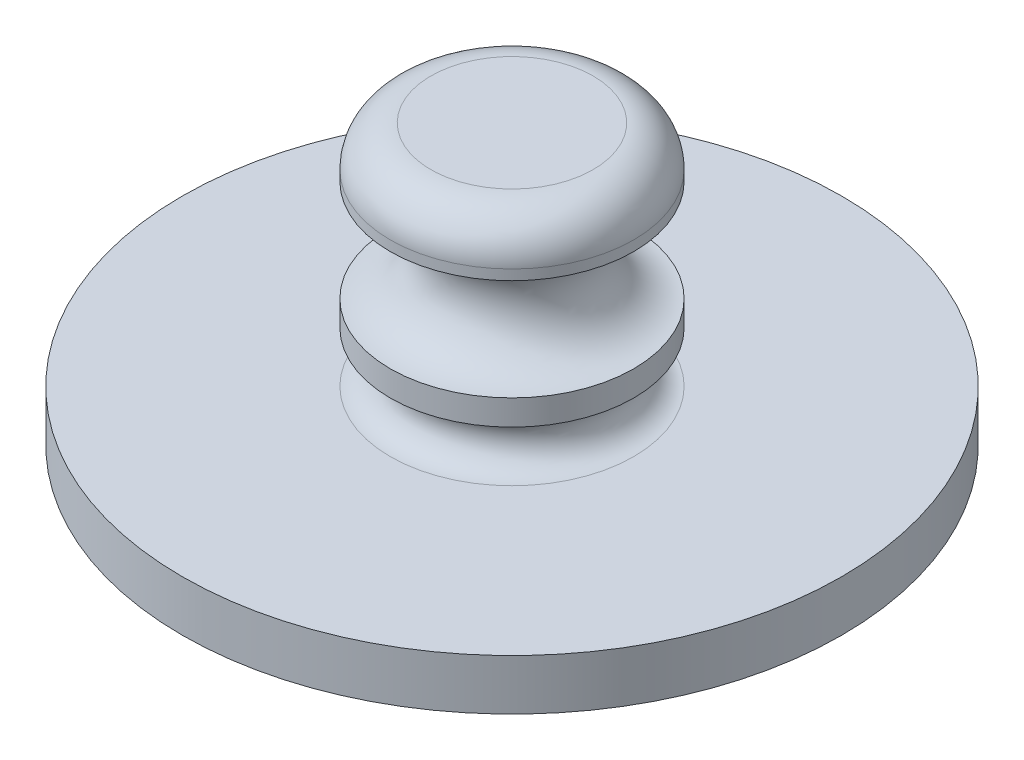
SolidWorks part; units mm, degrees
ref_plane "Front Plane" through (0, 0, 0) normal (0, 0, 1) x (1, 0, 0)
ref_plane "Top Plane" through (0, 0, 0) normal (0, 1, 0) x (1, 0, 0)
ref_plane "Right Plane" through (0, 0, 0) normal (1, 0, 0) x (0, 0, -1)
sketch "Sketch1" plane through (0, 0, 0) normal (0, 0, 1) x (1, 0, 0)
  line L0 (0, 0) -> (0, 77101.525) construction
  line L2 (0, 0) -> (6.5, 0)
  line L3 (0, 0) -> (0, 1)
  line L4 (2.4, 1) -> (6.5, 1)
  line L5 (6.5, 0) -> (6.5, 1)
  line L6 (0, 1) -> (0, 5.5)
  line L7 (0, 5.5) -> (1.6, 5.5)
  line L8 (2.4, 2) -> (2.4, 2.5)
  line L9 (2.4, 4.5) -> (2.4, 4.7)
  line L10 (0, 1) -> (2.4, 1) construction
  arc A0 (2.4, 1) -> (2.4, 2) centre (2.4, 1.5) cw
  arc A1 (2.4, 2.5) -> (2.4, 4.5) centre (2.4, 3.5) cw
  arc A2 (1.6, 5.5) -> (2.4, 4.7) centre (1.6, 4.7) cw
  point P19 (2.4, 5.5)
  point P20 (1.4, 3.5)
  dimension "D8" = 0.8
  dimension "D1" = 1
  dimension "D2" = 6.5
  dimension "D3" = 1.4
  dimension "D4" = 1
  dimension "D5" = 2
  dimension "D6" = 0.5
  dimension "D7" = 1
revolve "Revolve1" add sketch "Sketch1" angle 360 about L0
